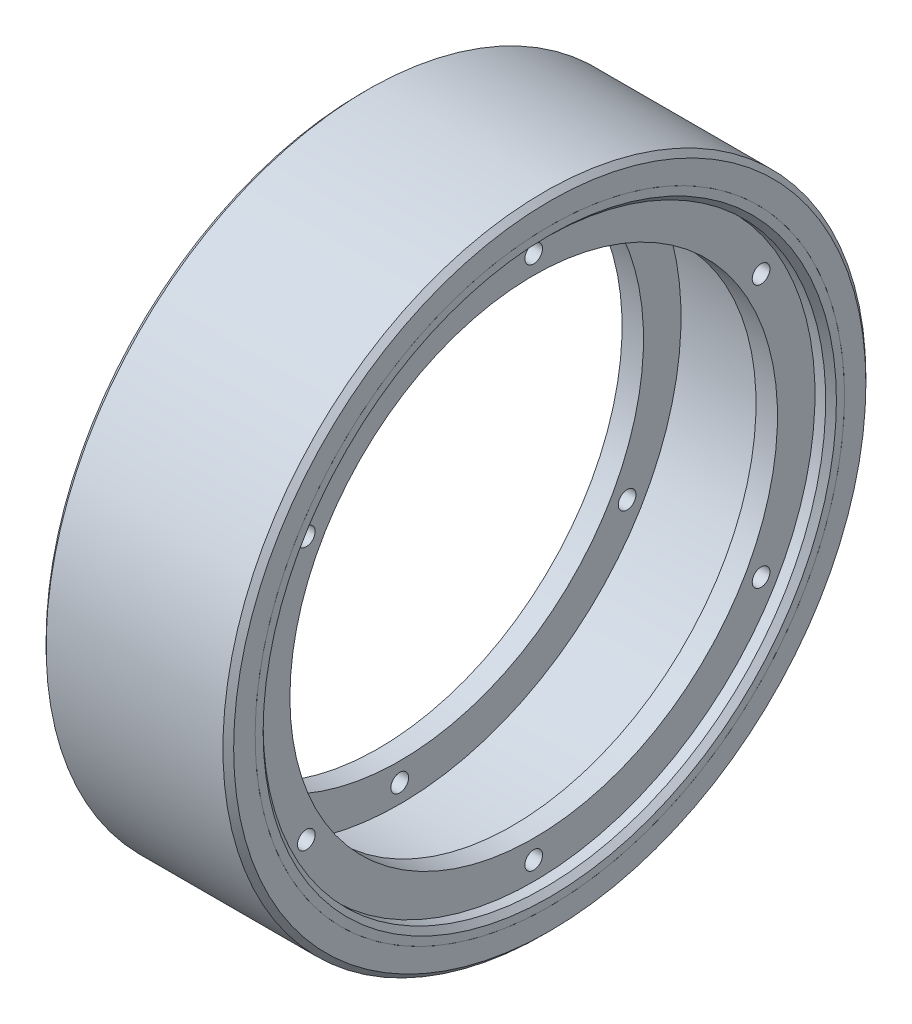
SolidWorks part; units mm, degrees
ref_plane "前视基准面" through (0, 0, 0) normal (0, 0, 1) x (1, 0, 0)
ref_plane "上视基准面" through (0, 0, 0) normal (0, 1, 0) x (1, 0, 0)
ref_plane "右视基准面" through (0, 0, 0) normal (1, 0, 0) x (0, 0, -1)
sketch "草图1" plane through (0, 0, 0) normal (1, 0, 0) x (0, 0, -1)
  circle A0 centre (0, 0) radius 60
  circle A1 centre (0, 0) radius 55
  dimension "D1" = 120
  dimension "D2" = 5
extrude "凸台-拉伸1" add sketch "草图1" along normal mid plane 35
sketch "草图2" plane through (0, 0, 0) normal (0, 0, 1) x (1, 0, 0)
  line L1 (17.5, 55) -> (-17.5, 55) construction
  line L2 (17.5, -60) -> (17.5, 60) construction
  line L3 (17.5, 55) -> (-17.5, 55)
  line L4 (-17.5, 60) -> (-17.5, -60) construction
  line L5 (17.5, 52.5) -> (17.5, 55)
  line L6 (-17.5, 55) -> (-17.5, 52.5)
  line L7 (-17.5, 52.5) -> (-14.5, 52.5)
  line L8 (-14.5, 52.5) -> (-14.5, 45.5)
  line L9 (-14.5, 45.5) -> (-10.5, 45.5)
  line L10 (14.5, 45.5) -> (14.5, 52.5)
  line L11 (14.5, 52.5) -> (17.5, 52.5)
  line L12 (0, 0) -> (30.828, 0) construction
  line L13 (10.5, 45.5) -> (14.5, 45.5)
  line L15 (-10.5, 45.5) -> (-10.5, 52.5)
  line L16 (-10.5, 52.5) -> (10.5, 52.5)
  line L17 (10.5, 45.5) -> (10.5, 52.5)
  dimension "D1" = 7
  dimension "D3" = 3
  dimension "D4" = 4
  dimension "D5" = 2.5
revolve "旋转1" add sketch "草图2" angle 360 about L12
hole_wizard "M4 螺纹孔1" positions "草图4" profile "草图5" tap size "M4" standard "GB" end condition through all
sketch "草图4" plane through (-14.5, 0, 0) normal (-1, 0, 0) x (0, 0, 1)
  circle A0 centre (0, 0) radius 49 construction
  circle A1 centre (0, 0) radius 45.5 construction
  point P0 (0, 49)
  point P14 (42.4352, 24.5)
  point P15 (42.4352, -24.5)
  point P16 (0, -49)
  point P17 (-42.4352, -24.5)
  point P18 (-42.4352, 24.5)
  dimension "D1" = 3.5
  dimension "D2" = 6
sketch "草图5" plane through (-14.5, 49, 0) normal (0, 1, 0) x (0, 0, 1)
  line L0 (0, 0) -> (0, 32)
  line L1 (0, 32) -> (1.65, 32)
  line L2 (1.65, 32) -> (1.65, 0)
  line L5 (1.65, 0) -> (0, 0)
  line L11 (0, -6.35) -> (0, 107.95) construction
  dimension "通孔螺纹孔钻头直径" = 3.3
  dimension "通孔螺纹孔钻头深度" = 32
cosmetic thread "孔螺蚊线1" parameters "D2"=4
cosmetic thread "孔螺蚊线2" parameters "D2"=4
cosmetic thread "孔螺蚊线3" parameters "D2"=4
cosmetic thread "孔螺蚊线4" parameters "D2"=4
cosmetic thread "孔螺蚊线5" parameters "D2"=4
cosmetic thread "孔螺蚊线6" parameters "D2"=4
chamfer "倒角1" distance 1 2 edges at (17.5, 0, -60) (-17.5, 0, -60)
chamfer "倒角2" distance 1 angle 45 2 edges at (17.5, 0, 52.5) (-17.5, 0, 52.5)
